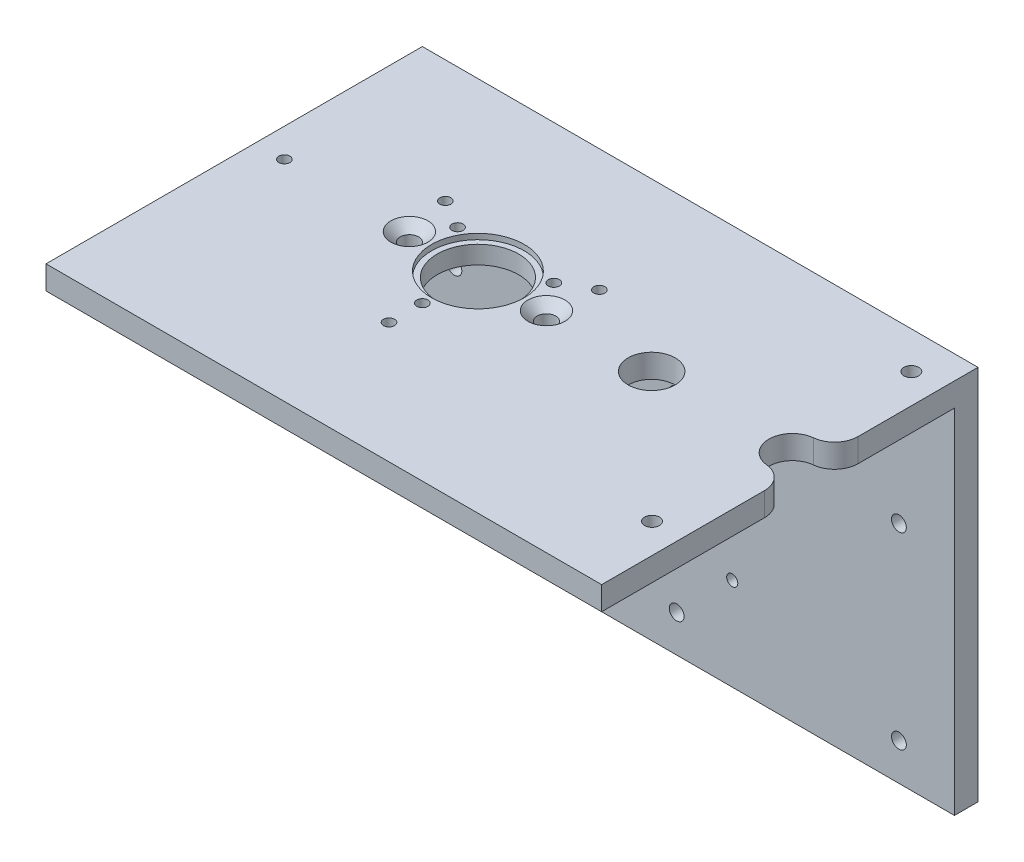
SolidWorks part; units mm, degrees
ref_plane "Alzado" through (0, 0, 0) normal (0, 0, 1) x (1, 0, 0)
ref_plane "Planta" through (0, 0, 0) normal (0, 1, 0) x (1, 0, 0)
ref_plane "Vista lateral" through (0, 0, 0) normal (1, 0, 0) x (0, 0, -1)
sketch "Croquis1" plane through (0, 0, 0) normal (0, 1, 0) x (1, 0, 0)
  line L1 (-75, 50.8) -> (75, 50.8)
  line L2 (-75, 50.8) -> (-75, -50.8)
  line L3 (-75, -50.8) -> (75, -50.8)
  line L4 (75, 50.8) -> (75, -50.8)
  line L5 (-75, 50.8) -> (75, -50.8) construction
  line L6 (-75, -50.8) -> (75, 50.8) construction
  point P0 (0, 0)
  dimension "D1" = 101.6
  dimension "D2" = 150
extrude "Saliente-Extruir1" add sketch "Croquis1" along normal mid plane 6.35
sketch "Croquis2" plane through (0, 3.175, 0) normal (0, 1, 0) x (1, 0, 0)
  line L0 (67, 50.8) -> (67, -50.8) construction
  line L1 (75, 50.8) -> (-75, 50.8) construction
  line L2 (-75, -50.8) -> (75, -50.8) construction
  line L3 (-75, 5.8) -> (75, 5.8) construction
  line L4 (-75, 50.8) -> (-75, -50.8) construction
  line L5 (75, -50.8) -> (75, 50.8) construction
  circle A0 centre (67, 40.8) radius 2
  circle A1 centre (67, -29.2) radius 2
  circle A2 centre (-15, 5.8) radius 11
  circle A3 centre (-67.25, 5.8) radius 1.5
  circle A4 centre (31.9, 5.8) radius 6.35
  circle A5 centre (69.9, 5.8) radius 6.35
  dimension "D3" = 4
  dimension "D6" = 22
  dimension "D7" = 3
  dimension "D9" = 12.7
  dimension "D2" = 8
  dimension "D4" = 35
  dimension "D5" = 82
  dimension "D8" = 52.25
  dimension "D10" = 46.9
  dimension "D11" = 84.9
  dimension "D12" = 45
extrude "Cortar-Extruir1" cut sketch "Croquis2" against normal through all
fillet "Redondeo1" radius 6.35 2 edges at (75, 0, -9.5832) (75, 0, -2.0168)
sketch "Croquis3" plane through (0, 3.175, 0) normal (0, 1, 0) x (1, 0, 0)
  line L0 (-15, 5.8) -> (-15, -18.2) construction
  circle A0 centre (-15, -9.2) radius 1.5
  circle A1 centre (-15, -18.2) radius 1.5
  circle A2 centre (-15, 5.8) radius 20 construction
  circle A3 centre (-15, -18.2) radius 4 construction
  circle A4 centre (-27.9904, 13.3) radius 1.5
  circle A5 centre (-35.7846, 17.8) radius 1.5
  circle A6 centre (-2.0096, 13.3) radius 1.5
  circle A7 centre (5.7846, 17.8) radius 1.5
  point P19 (-15, 5.8)
  dimension "D1" = 3
  dimension "D2" = 3
  dimension "D5" = 40
  dimension "D6" = 8
  dimension "D3" = 15
  dimension "D4" = 24
  dimension "D7" = 3
extrude "Cortar-Extruir2" cut sketch "Croquis3" against normal through all
sketch "Croquis4" plane through (0, 0, 0) normal (0, 1, 0) x (1, 0, 0)
  circle A0 centre (-15, 5.8) radius 12.5
  dimension "D1" = 25
extrude "Cortar-Extruir3" cut sketch "Croquis4" against normal blind 1.5 from surface at 3.175 starting at face at (5.7846, 3.175, -16.3)
sketch "Croquis5" plane through (0, -3.175, 0) normal (0, -1, 0) x (1, 0, 0)
  line L0 (0, 0) -> (0, -50.8) construction
  line L1 (75, -50.8) -> (-75, -50.8) construction
  line L3 (-75, -44.45) -> (75, -44.45)
  line L4 (-75, -44.45) -> (-75, -50.8)
  line L5 (-75, -50.8) -> (75, -50.8)
  line L6 (75, -44.45) -> (75, -50.8)
  line L7 (-75, -44.45) -> (75, -50.8) construction
  line L8 (-75, -50.8) -> (75, -44.45) construction
  point P5 (0, -47.625)
  dimension "D1" = 6.35
extrude "Saliente-Extruir2" add sketch "Croquis5" along normal blind 101.6 from surface at -6.35 starting at face at (-15, 3.175, 6.7)
sketch "Croquis7" plane through (0, 0, -50.8) normal (0, 0, -1) x (-1, 0, 0)
  line L0 (0, 3.175) -> (0, -98.425) construction
  line L1 (-75, 3.175) -> (75, 3.175) construction
  line L2 (-75, -98.425) -> (75, -98.425) construction
  line L3 (-75, -6.825) -> (75, -6.825) construction
  line L4 (-75, 3.175) -> (-75, -98.425) construction
  line L5 (75, 3.175) -> (75, -98.425) construction
  line L6 (0, -47.625) -> (-75, -47.625) construction
  line L7 (-60, -88.425) -> (-60, -37.625) construction
  line L8 (-60, -37.625) -> (0, -37.625) construction
  circle A0 centre (-60, -6.825) radius 2
  circle A1 centre (0, -6.825) radius 2
  circle A2 centre (60, -6.825) radius 2
  circle A3 centre (60, -88.425) radius 2
  circle A4 centre (0, -88.425) radius 2
  circle A5 centre (-60, -88.425) radius 2
  circle A6 centre (-60, -37.625) radius 2
  circle A7 centre (0, -37.625) radius 2
  circle A8 centre (60, -37.625) radius 2
  dimension "D3" = 4
  dimension "D1" = 10
  dimension "D2" = 15
  dimension "D4" = 10
extrude "Cortar-Extruir5" cut sketch "Croquis7" against normal through all
sketch "Croquis9" plane through (0, 3.175, 0) normal (0, 1, 0) x (1, 0, 0)
  line L0 (-15, 16.8) -> (-15, 5.8) construction
  line L1 (-15, 5.8) -> (3.5, 5.8) construction
  circle A0 centre (-15, 5.8) radius 11 construction
  circle A1 centre (3.5, 5.8) radius 2.5
  circle A2 centre (-33.5, 5.8) radius 2.5
  dimension "D2" = 5
  dimension "D1" = 18.5
extrude "Cortar-Extruir6" cut sketch "Croquis9" against normal through all
chamfer "Chaflán1" distance 2.5 angle 45 2 edges at (-33.5, 3.175, -8.3) (3.5, 3.175, -3.3)
sketch "Croquis10" plane through (0, 0, -44.45) normal (0, 0, 1) x (1, 0, 0)
  line L0 (75, -73.425) -> (-15, -73.425) construction
  line L1 (75, -98.425) -> (75, -3.175) construction
  line L2 (-15, -73.425) -> (-15, -98.425) construction
  line L3 (-75, -98.425) -> (75, -98.425) construction
  line L4 (-75, -78.425) -> (75, -78.425) construction
  line L5 (-75, -98.425) -> (-75, -3.175) construction
  circle A1 centre (15, -73.425) radius 1.5
  circle A2 centre (-45, -73.425) radius 1.5
  dimension "D5" = 3
  dimension "D1" = 90
  dimension "D2" = 20
  dimension "D3" = 25
  dimension "D4" = 30
extrude "Cortar-Extruir7" cut sketch "Croquis10" against normal through all
sketch "Croquis11" plane through (0, 3.175, 0) normal (0, 1, 0) x (1, 0, 0)
  line L0 (-15, 30.8) -> (-15, 107.4) construction
  line L1 (-75, 30.8) -> (75, 30.8) construction
  line L2 (-75, 50.8) -> (-75, -50.8) construction
  line L3 (75, 18.4383) -> (75, 50.8) construction
  line L4 (75, 50.8) -> (-75, 50.8) construction
  circle A0 centre (-15, 5.8) radius 101.6 construction
  dimension "D1" = 203.2
  dimension "D2" = 20
